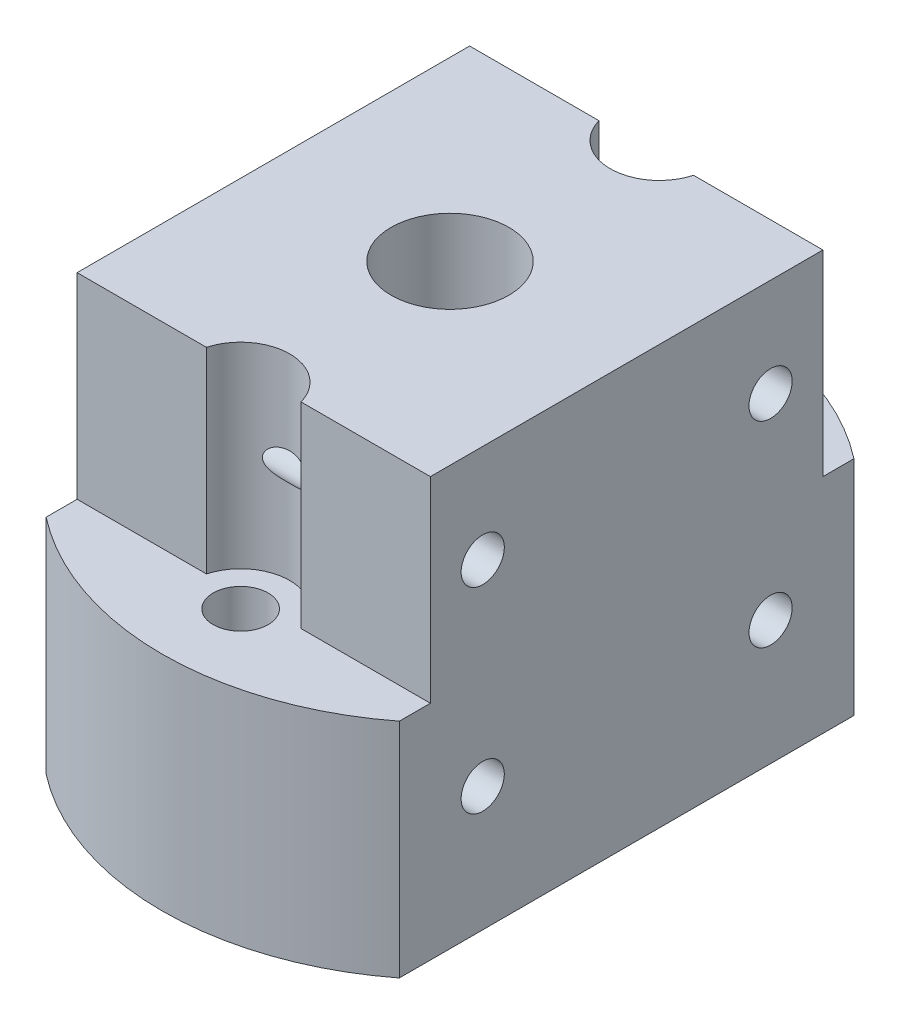
SolidWorks part; units mm, degrees
material "ABS"
ref_plane "前视基准面" through (0, 0, 0) normal (0, 0, 1) x (1, 0, 0)
ref_plane "上视基准面" through (0, 0, 0) normal (0, 1, 0) x (1, 0, 0)
ref_plane "右视基准面" through (0, 0, 0) normal (1, 0, 0) x (0, 0, -1)
other "Configuration Table"
sketch "草图1" plane through (0, 0, 0) normal (0, 1, 0) x (1, 0, 0)
  line L0 (0, 22) -> (0, -22) construction
  line L2 (-13.5, -17.371) -> (-13.5, 17.371)
  line L4 (13.5, -17.371) -> (13.5, 17.371)
  line L5 (-13.5, -17.371) -> (13.5, 17.371) construction
  line L6 (-13.5, 17.371) -> (13.5, -17.371) construction
  line L7 (0, 16) -> (0, -16) construction
  arc A0 (-13.5, -17.371) -> (13.5, -17.371) centre (0, 0) ccw
  arc A1 (13.5, 17.371) -> (-13.5, 17.371) centre (0, 0) ccw
  circle A2 centre (0, 16) radius 2.1
  circle A3 centre (0, -16) radius 2.1
  circle A4 centre (0, 0) radius 8.15
  dimension "D1" = 44
  dimension "D3" = 4.2
  dimension "D4" = 32
  dimension "D5" = 16.3
  dimension "D2" = 27
extrude "凸台-拉伸1" add sketch "草图1" along normal blind 17
sketch "草图2" plane through (0, 17, 0) normal (0, 1, 0) x (1, 0, 0)
  line L0 (13.5, -17.371) -> (13.5, 17.371) construction
  line L1 (-13.5, -15) -> (13.5, -15)
  line L2 (-13.5, -15) -> (-13.5, 15)
  line L3 (-13.5, 15) -> (13.5, 15)
  line L4 (13.5, -15) -> (13.5, 15)
  line L5 (-13.5, -15) -> (13.5, 15) construction
  line L6 (-13.5, 15) -> (13.5, -15) construction
  point P0 (0, 0)
  dimension "D1" = 30
extrude "凸台-拉伸2" add sketch "草图2" along normal blind 15
sketch "草图3" plane through (0, 32, 0) normal (0, 1, 0) x (1, 0, 0)
  circle A0 centre (0, 16) radius 3.75
  circle A1 centre (0, -16) radius 3.75
  dimension "D1" = 7.5
extrude "切除-拉伸2" cut sketch "草图3" against normal up to surface (15 mm away) up to face at (0, 17, -17.0785)
sketch "草图4" plane through (-13.5, 0, 0) normal (-1, 0, 0) x (0, 0, 1)
  line L0 (11, 32) -> (11, 0) construction
  line L1 (-15, 32) -> (15, 32) construction
  line L2 (-17.371, 0) -> (17.371, 0) construction
  line L3 (15, 32) -> (15, 17) construction
  line L4 (0, 0) -> (0, 32) construction
  circle A0 centre (11, 24.5) radius 1.65
  circle A1 centre (-11, 24.5) radius 1.65
  circle A2 centre (11, 9.5) radius 1.65
  circle A3 centre (-11, 9.5) radius 1.65
  dimension "D2" = 3.3
  dimension "D3" = 7.5
  dimension "D4" = 15
  dimension "D1" = 4
extrude "切除-拉伸3" cut sketch "草图4" against normal through all
sketch "草图5" plane through (0, 32, 0) normal (0, 1, 0) x (1, 0, 0)
  circle A0 centre (0, 0) radius 4.5
  dimension "D1" = 9
extrude "切除-拉伸4" cut sketch "草图5" against normal through all
